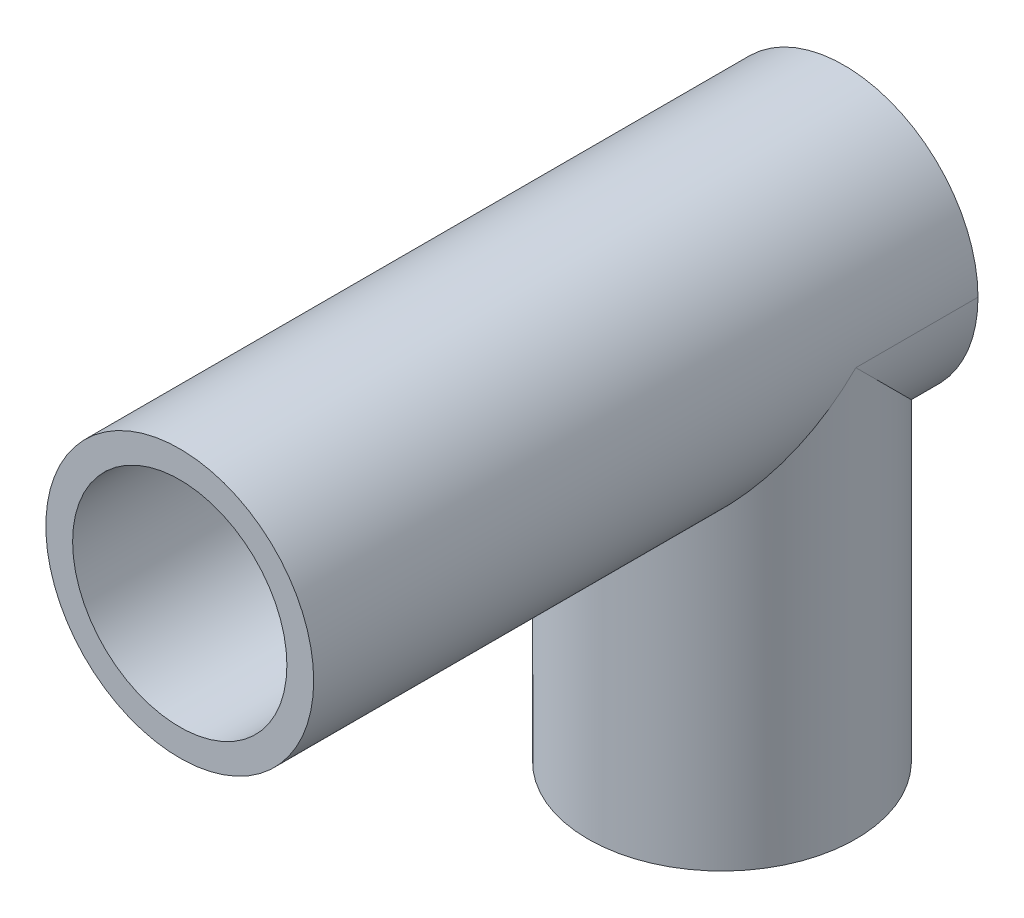
SolidWorks part; units mm, degrees
ref_plane "Front Plane" through (0, 0, 0) normal (0, 0, 1) x (1, 0, 0)
ref_plane "Top Plane" through (0, 0, 0) normal (0, 1, 0) x (1, 0, 0)
ref_plane "Right Plane" through (0, 0, 0) normal (1, 0, 0) x (0, 0, -1)
sketch "Sketch1" plane through (0, 0, 0) normal (0, 1, 0) x (1, 0, 0)
  circle A0 centre (0, 0) radius 20
  circle A1 centre (0, 0) radius 25
  dimension "D1" = 50
  dimension "D2" = 40
extrude "Boss-Extrude1" add sketch "Sketch1" along normal blind 76.2
ref_plane "Plane1" through (0, 0, 25) normal (0, 0, 1) x (1, 0, 0)
sketch "Sketch2" plane through (0, 0, 25) normal (0, 0, 1) x (1, 0, 0)
  line L0 (25, 76.2) -> (-25, 76.2) construction
  circle A0 centre (0, 76.2) radius 25
  circle A1 centre (0, 76.2) radius 20
  dimension "D1" = 50
  dimension "D2" = 40
extrude "Boss-Extrude2" add sketch "Sketch2" along normal blind 76.2 and the other way blind 50
sketch "Sketch3" plane through (0, 0, 101.2) normal (0, 0, 1) x (1, 0, 0)
  line L0 (20, 76.2) -> (-20, 76.2) construction
  circle A0 centre (0, 76.2) radius 20
  arc A1 (-20, 76.2) -> (20, 76.2) centre (0, 76.2) ccw construction
extrude "Cut-Extrude1" cut sketch "Sketch3" against normal blind 145.2
sketch "Sketch4" plane through (0, 0, -25) normal (0, 0, -1) x (-1, 0, 0)
  circle A0 centre (0, 76.2) radius 25
  circle A1 centre (0, 76.2) radius 25 construction
extrude "Cut-Extrude2" cut sketch "Sketch4" against normal blind 2.2
sketch "Sketch5" plane through (0, 0, -22.8) normal (0, 0, -1) x (-1, 0, 0)
  circle A0 centre (0, 76.2) radius 20
  circle A1 centre (0, 76.2) radius 20 construction
extrude "Boss-Extrude3" add sketch "Sketch5" against normal blind 2.54
